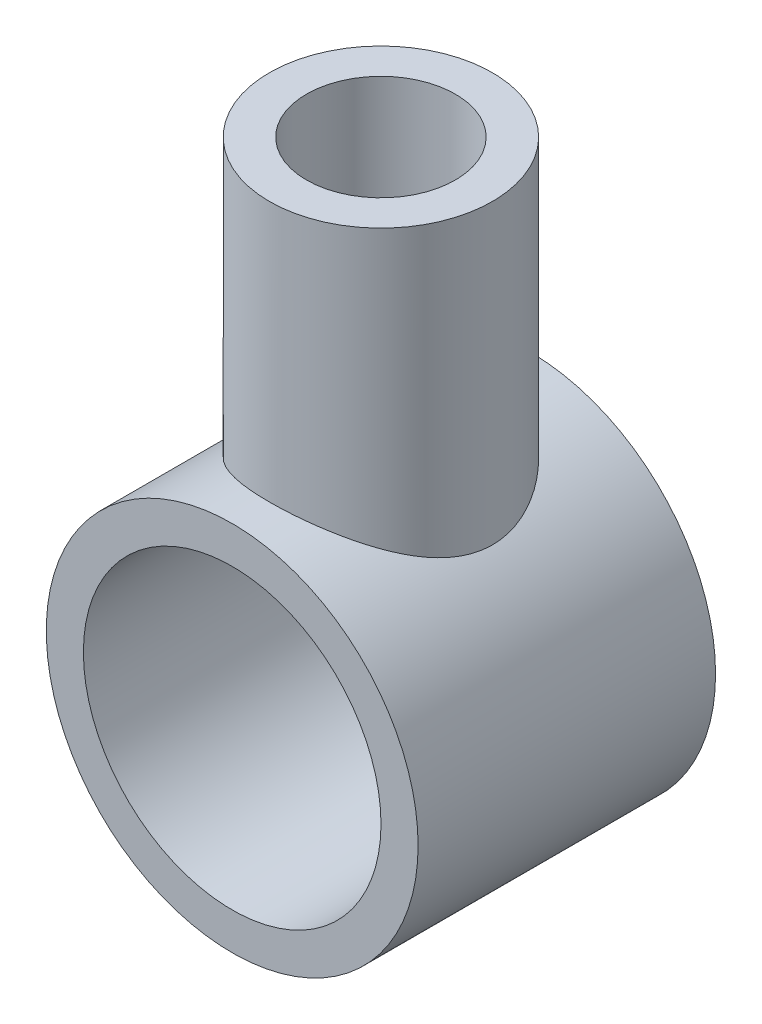
SolidWorks part; units mm, degrees
ref_plane "Front Plane" through (0, 0, 0) normal (0, 0, 1) x (1, 0, 0)
ref_plane "Top Plane" through (0, 0, 0) normal (0, 1, 0) x (1, 0, 0)
ref_plane "Right Plane" through (0, 0, 0) normal (1, 0, 0) x (0, 0, -1)
sketch "Sketch1" plane through (0, 0, 0) normal (0, 0, 1) x (1, 0, 0)
  circle A0 centre (0, 0) radius 12.5
  dimension "D1" = 25
ref_plane "Plane1" through (0, 30, 0) normal (0, 1, 0) x (1, 0, 0)
sketch "Sketch3" plane through (0, 30, 0) normal (0, 1, 0) x (1, 0, 0)
  circle A0 centre (0, 0) radius 7.5
  dimension "D1" = 15
extrude "Boss-Extrude1" add sketch "Sketch3" against normal blind 22
extrude "Boss-Extrude2" add sketch "Sketch1" along normal blind 10 and the other way blind 10 contours A0
sketch "Sketch5" plane through (0, 30, 0) normal (0, 1, 0) x (1, 0, 0)
  circle A0 centre (0, 0) radius 5.005
  dimension "D1" = 10.01
sketch "Sketch6" plane through (0, 0, -10) normal (0, 0, -1) x (-1, 0, 0)
  circle A0 centre (0, 0) radius 10.005
  dimension "D1" = 20.01
extrude "Cut-Extrude1" cut sketch "Sketch6" against normal blind 49
extrude "Cut-Extrude2" cut sketch "Sketch5" against normal blind 15 contours A0
